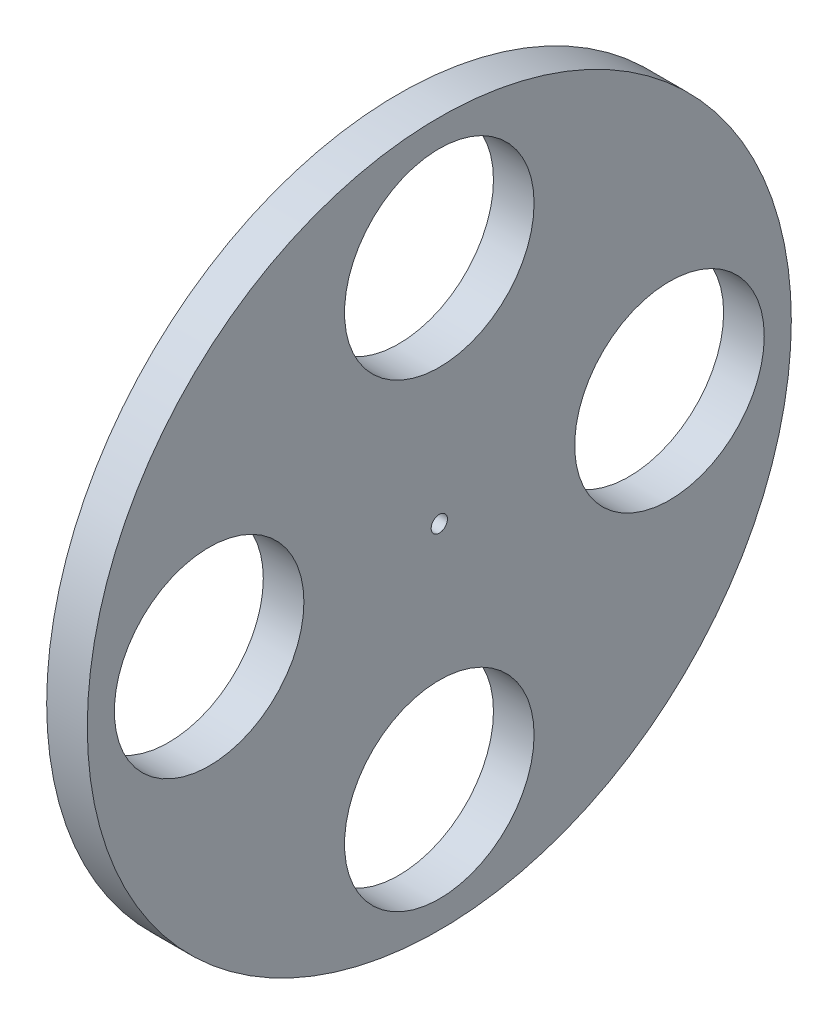
SolidWorks part; units mm, degrees
ref_plane "Plan de face" through (0, 0, 0) normal (0, 0, 1) x (1, 0, 0)
ref_plane "Plan de dessus" through (0, 0, 0) normal (0, 1, 0) x (1, 0, 0)
ref_plane "Plan de droite" through (0, 0, 0) normal (1, 0, 0) x (0, 0, -1)
sketch "Esquisse2" plane through (0, 0, 0) normal (1, 0, 0) x (0, 0, -1)
  circle A0 centre (0, 0) radius 130
extrude "Boss.-Extru.1" add sketch "Esquisse2" along normal blind 15
sketch "Esquisse3" plane through (15, 0, 0) normal (1, 0, 0) x (0, 0, -1)
  circle A0 centre (0, 85) radius 35
  circle A1 centre (0, 0) radius 130 construction
  circle A2 centre (85, 0) radius 35
  circle A3 centre (0, -85) radius 35
  circle A4 centre (-85, 0) radius 35
  dimension "D1" = 85
  dimension "D2" = 85
  dimension "D3" = 85
  dimension "D4" = 85
extrude "Enlèv. mat.-Extru.1" cut sketch "Esquisse3" against normal blind 15
sketch "Esquisse4" plane through (15, 0, 0) normal (1, 0, 0) x (0, 0, -1)
  circle A0 centre (0, 0) radius 3
extrude "Enlèv. mat.-Extru.3" cut sketch "Esquisse4" against normal blind 24
